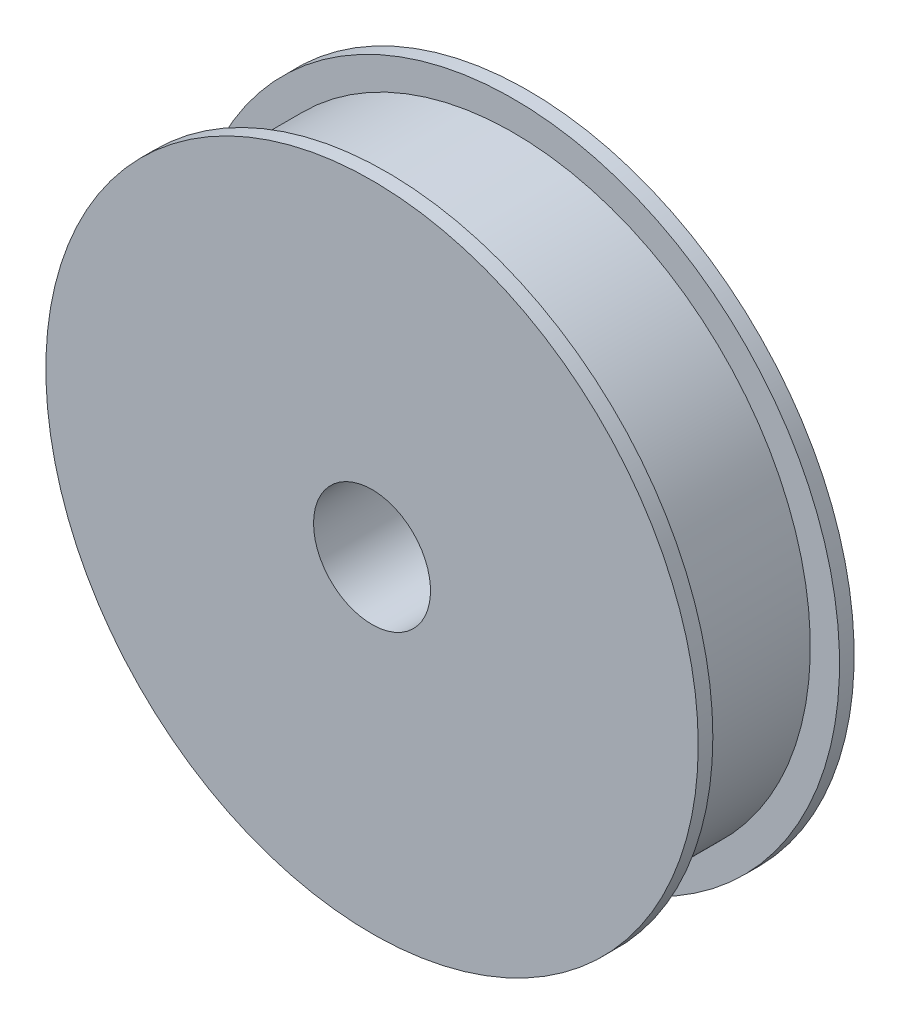
SolidWorks part; units mm, degrees
material "SKD11淬火HRC56-60"
ref_plane "前基準面" through (0, 0, 0) normal (0, 0, 1) x (1, 0, 0)
ref_plane "上基準面" through (0, 0, 0) normal (0, 1, 0) x (1, 0, 0)
ref_plane "右基準面" through (0, 0, 0) normal (1, 0, 0) x (0, 0, -1)
sketch "草图1" plane through (0, 0, 0) normal (0, 0, 1) x (1, 0, 0)
  circle A0 centre (0, 0) radius 30.47
  dimension "D1" = 60.94
extrude "凸台-拉伸1" add sketch "草图1" along normal blind 13
sketch "草图2" plane through (0, 0, 13) normal (0, 0, 1) x (1, 0, 0)
  circle A0 centre (0, 0) radius 33.47
  circle A1 centre (0, 0) radius 30.47 construction
  dimension "D1" = 3
extrude "凸台-拉伸2" add sketch "草图2" along normal blind 1.5
sketch "草图3" plane through (0, 0, 0) normal (0, 0, -1) x (-1, 0, 0)
  circle A0 centre (0, 0) radius 33.47
  circle A1 centre (0, 0) radius 30.47 construction
  dimension "D1" = 3
extrude "凸台-拉伸3" add sketch "草图3" along normal blind 1.5
sketch "草图4" plane through (0, 0, -1.5) normal (0, 0, -1) x (-1, 0, 0)
  circle A0 centre (0, 0) radius 6
  dimension "D1" = 12
extrude "切除-拉伸1" cut sketch "草图4" against normal through all
sketch "草图5" plane through (0, 0, -1.5) normal (0, 0, -1) x (-1, 0, 0)
  circle A0 centre (0, 0) radius 10
  dimension "D1" = 20
extrude "切除-拉伸2" cut sketch "草图5" against normal blind 5
